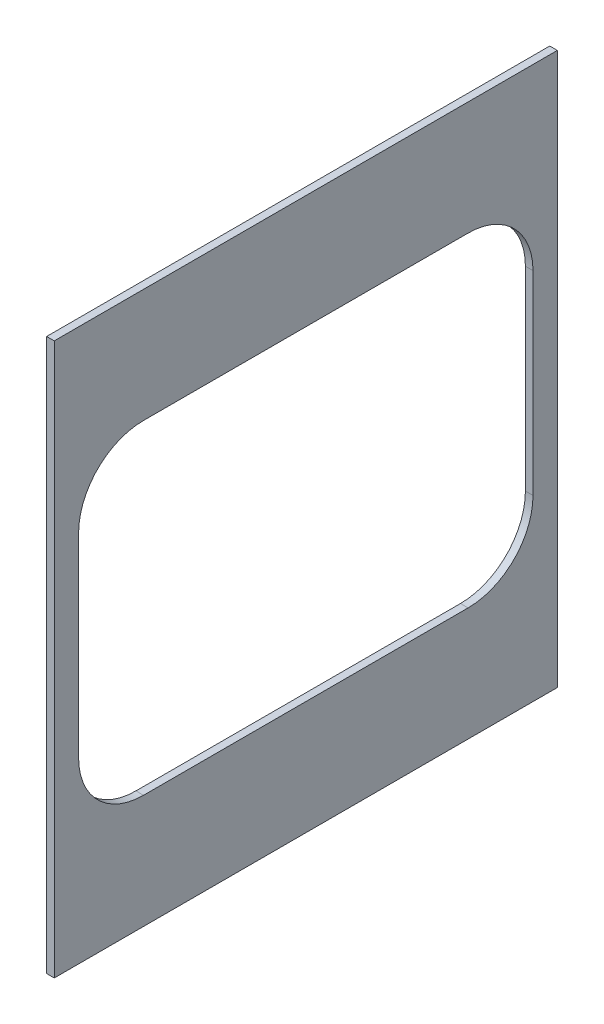
SolidWorks part; units mm, degrees
material "Pine"
ref_plane "Front Plane" through (0, 0, 0) normal (0, 0, 1) x (1, 0, 0)
ref_plane "Top Plane" through (0, 0, 0) normal (0, 1, 0) x (1, 0, 0)
ref_plane "Right Plane" through (0, 0, 0) normal (1, 0, 0) x (0, 0, -1)
sketch "Sketch1" plane through (0, 0, 0) normal (1, 0, 0) x (0, 0, -1)
  line L0 (38.1, 279.4) -> (0, 279.4) construction
  line L1 (0, 0) -> (787.4, 0)
  line L2 (0, 0) -> (0, 863.6)
  line L3 (0, 863.6) -> (787.4, 863.6)
  line L4 (787.4, 0) -> (787.4, 863.6)
  line L5 (139.7, 685.8) -> (647.7, 685.8)
  line L6 (38.1, 584.2) -> (38.1, 279.4)
  line L7 (139.7, 177.8) -> (647.7, 177.8)
  line L8 (749.3, 584.2) -> (749.3, 279.4)
  line L9 (749.3, 279.4) -> (787.4, 279.4) construction
  arc A4 (38.1, 279.4) -> (139.7, 177.8) centre (139.7, 279.4) ccw
  arc A5 (647.7, 177.8) -> (749.3, 279.4) centre (647.7, 279.4) ccw
  arc A6 (647.7, 685.8) -> (749.3, 584.2) centre (647.7, 584.2) cw
  arc A7 (139.7, 685.8) -> (38.1, 584.2) centre (139.7, 584.2) ccw
  point P24 (38.1, 177.8)
  point P27 (749.3, 177.8)
  point P30 (749.3, 685.8)
  dimension "D12" = 101.6
  dimension "D1" = 863.6
  dimension "D2" = 787.4
  dimension "D3" = 177.8
  dimension "D4" = 711.2
  dimension "D5" = 508
extrude "Boss-Extrude1" add sketch "Sketch1" along normal blind 11.9062
